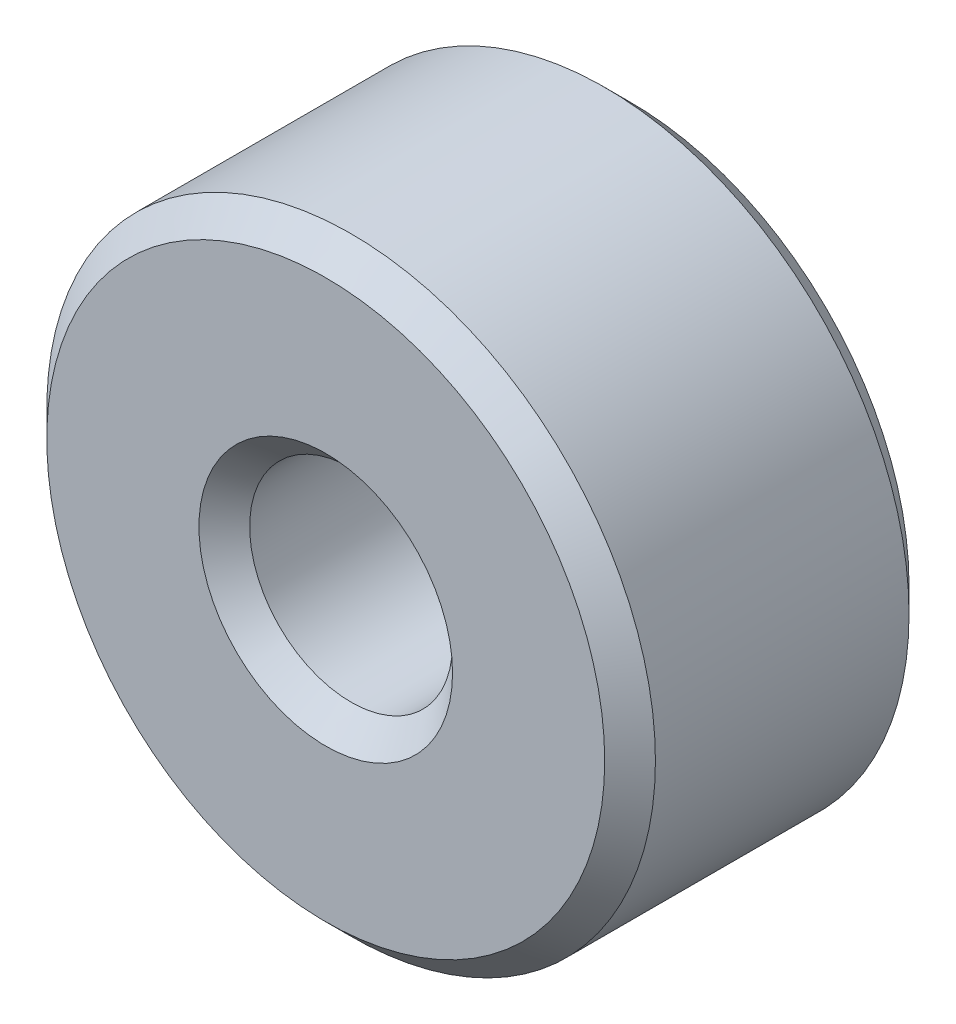
SolidWorks part; units mm, degrees
ref_plane "Front Plane" through (0, 0, 0) normal (0, 0, 1) x (1, 0, 0)
ref_plane "Top Plane" through (0, 0, 0) normal (0, 1, 0) x (1, 0, 0)
ref_plane "Right Plane" through (0, 0, 0) normal (1, 0, 0) x (0, 0, -1)
sketch "Sketch1" plane through (0, 0, 0) normal (0, 0, 1) x (1, 0, 0)
  circle A0 centre (0, 0) radius 1
  dimension "D1" = 2
extrude "Extrude-Thin1" add sketch "Sketch1" along normal blind 3 thin
chamfer "Chamfer1" distance 0.25 angle 45 4 edges at (1, 0, 0) (3, 0, 0) (1, 0, 3) (3, 0, 3)
scale "Scale1" scale about centroid uniform scaling yes scale factor 0.445
